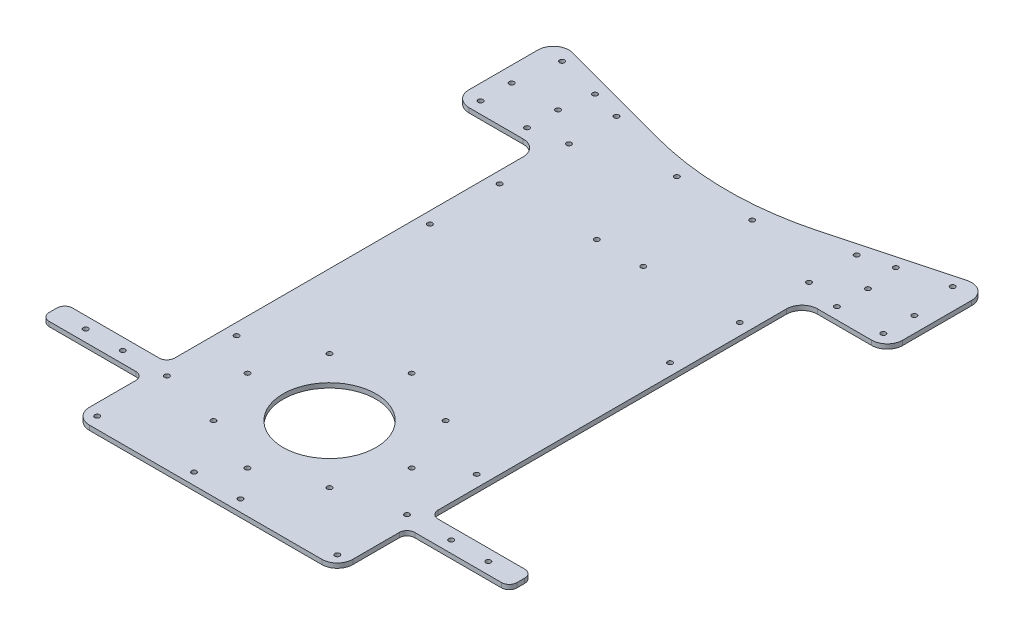
SolidWorks part; units mm, degrees
ref_plane "Front Plane" through (0, 0, 0) normal (0, 0, 1) x (1, 0, 0)
ref_plane "Top Plane" through (0, 0, 0) normal (0, 1, 0) x (1, 0, 0)
ref_plane "Right Plane" through (0, 0, 0) normal (1, 0, 0) x (0, 0, -1)
sketch "Sketch1" plane through (0, 0, 0) normal (0, 1, 0) x (1, 0, 0)
  line L4 (0, 0) -> (170, 0)
  line L5 (0, 0) -> (0, 330) construction
  line L6 (0, 330) -> (170, 330) construction
  line L7 (170, 0) -> (170, 330) construction
  line L8 (85, 330) -> (225, 367.5129)
  line L9 (-55, 367.5129) -> (85, 330)
  line L10 (-55, 367.5129) -> (-55, 300)
  line L11 (-55, 300) -> (0, 300)
  line L12 (225, 300) -> (225, 367.5129)
  line L13 (225, 300) -> (170, 300)
  line L14 (0, 300) -> (0, 0)
  line L15 (170, 300) -> (170, 0)
  dimension "D1" = 30
  dimension "D2" = 330
  dimension "D3" = 15
  dimension "D4" = 15
  dimension "D5" = 55
  dimension "D6" = 170
extrude "Boss-Extrude1" add sketch "Sketch1" along normal blind 3
fillet "Fillet1" radius 200 1 edges at (85, 1.5, -330)
fillet "Fillet2" radius 10 8 edges at (0, 1.5, 0) (170, 1.5, 0) (170, 1.5, -300) (0, 1.5, -300) (-55, 1.5, -300) (225, 1.5, -300) (225, 1.5, -367.5129) (-55, 1.5, -367.5129)
sketch "Sketch2" plane through (0, 3, 0) normal (0, 1, 0) x (1, 0, 0)
  line L0 (85, 337.0552) -> (85, 0) construction
  line L1 (10, 0) -> (160, 0) construction
  arc A0 (33.2362, 343.8701) -> (136.7638, 343.8701) centre (85, 537.0552) ccw construction
  circle A1 centre (85, 80) radius 30
  dimension "D1" = 60
  dimension "D2" = 80
extrude "Cut-Extrude1" cut sketch "Sketch2" against normal through all
sketch "Sketch3" plane through (0, 3, 0) normal (0, 1, 0) x (1, 0, 0)
  line L0 (0, 290) -> (0, 10) construction
  line L1 (0, 45) -> (-66, 45)
  line L2 (0, 45) -> (0, 60)
  line L3 (0, 60) -> (-66, 60)
  line L4 (-66, 45) -> (-66, 60)
  line L5 (-66, 52.5) -> (7.5, 52.5) construction
  line L6 (7.5, 52.5) -> (7.5, 0) construction
  line L7 (10, 0) -> (160, 0) construction
  line L8 (-33, 60) -> (-33, 45) construction
  line L9 (85, 0) -> (85, 337.0552) construction
  line L10 (170, 60) -> (236, 60)
  line L11 (236, 45) -> (236, 60)
  line L12 (170, 45) -> (236, 45)
  line L13 (170, 45) -> (170, 60)
  circle A0 centre (-21, 52.5) radius 1.6
  circle A1 centre (-45, 52.5) radius 1.6
  arc A2 (33.2362, 343.8701) -> (136.7638, 343.8701) centre (85, 537.0552) ccw construction
  circle A3 centre (191, 52.5) radius 1.6
  circle A4 centre (215, 52.5) radius 1.6
  dimension "D2" = 12
  dimension "D6" = 3.2
  dimension "D7" = 12
  dimension "D1" = 66
  dimension "D3" = 7.5
  dimension "D4" = 52.5
  dimension "D5" = 15
extrude "Boss-Extrude2" add sketch "Sketch3" against normal blind 3
fillet "Fillet3" radius 5 8 edges at (236, 1.5, -45) (170, 1.5, -45) (236, 1.5, -60) (170, 1.5, -60) (0, 1.5, -45) (0, 1.5, -60) (-66, 1.5, -60) (-66, 1.5, -45)
sketch "Sketch4" plane through (0, 0, 0) normal (0, -1, 0) x (1, 0, 0)
  circle A0 centre (162.5, -7.5) radius 1.6
  circle A1 centre (162.5, -52.5) radius 1.6
  circle A2 centre (100, -7.5) radius 1.6
  circle A3 centre (70, -7.5) radius 1.6
  circle A4 centre (162.5, -97.5) radius 1.6
  circle A5 centre (162.5, -222.3) radius 1.6
  circle A6 centre (162.5, -267.3) radius 1.6
  circle A7 centre (162.5, -312) radius 1.6
  circle A8 centre (162.5, -342.755) radius 1.6
  circle A9 centre (109.3378, -328.5102) radius 1.6
  circle A10 centre (60.6622, -328.5102) radius 1.6
  circle A11 centre (7.5, -342.755) radius 1.6
  circle A12 centre (7.5, -312) radius 1.6
  circle A13 centre (7.5, -267.3) radius 1.6
  circle A14 centre (7.5, -222.3) radius 1.6
  circle A15 centre (7.5, -97.5) radius 1.6
  circle A16 centre (7.5, -52.5) radius 1.6
  circle A17 centre (7.5, -7.5) radius 1.6
  circle A18 centre (70, -267.5) radius 1.6
  circle A19 centre (100, -267.5) radius 1.6
  dimension "D1" = 3.2
extrude "Cut-Extrude2" cut sketch "Sketch4" against normal through all
sketch "Sketch5" plane through (0, 3, 0) normal (0, 1, 0) x (1, 0, 0)
  circle A0 centre (-40.837, 355.9533) radius 1.6
  circle A1 centre (-11.8592, 348.1888) radius 1.6
  circle A2 centre (182.2342, 348.2893) radius 1.6
  circle A3 centre (211.212, 356.0538) radius 1.6
  dimension "D1" = 3.2
extrude "Cut-Extrude3" cut sketch "Sketch5" against normal through all
sketch "Sketch7" plane through (0, 3, 0) normal (0, 1, 0) x (1, 0, 0)
  line L0 (-55, 335) -> (-5, 335) construction
  line L1 (-55, 354.4806) -> (-55, 310) construction
  line L2 (-5, 335) -> (-5, 300) construction
  line L3 (-45, 300) -> (-10, 300) construction
  line L4 (-45, 327.5) -> (-15, 327.5) construction
  line L5 (-15, 327.5) -> (-15, 307.5) construction
  line L6 (-15, 307.5) -> (-45, 307.5) construction
  line L7 (-45, 307.5) -> (-45, 327.5) construction
  line L8 (85, 337.0552) -> (85, 300) construction
  circle A0 centre (-45, 327.5) radius 1.6
  circle A1 centre (-45, 307.5) radius 1.6
  circle A2 centre (-15, 327.5) radius 1.6
  circle A3 centre (-15, 307.5) radius 1.6
  arc A4 (33.2362, 343.8701) -> (136.7638, 343.8701) centre (85, 537.0552) ccw construction
  circle A5 centre (185, 327.5) radius 1.6
  circle A6 centre (185, 307.5) radius 1.6
  circle A7 centre (215, 307.5) radius 1.6
  circle A8 centre (215, 327.5) radius 1.6
  dimension "D7" = 3.2
  dimension "D1" = 50
  dimension "D2" = 35
  dimension "D3" = 7.5
  dimension "D4" = 10
  dimension "D5" = 7.5
  dimension "D6" = 10
extrude "Cut-Extrude4" cut sketch "Sketch7" against normal through all
sketch "Sketch8" plane through (0, 3, 0) normal (0, 1, 0) x (1, 0, 0)
  line L0 (85, 133) -> (85, 80) construction
  circle A1 centre (85, 133) radius 1.6
  circle A2 centre (85, 80) radius 58 construction
  circle A3 centre (85, 80) radius 53 construction
  circle A4 centre (122.4767, 117.4767) radius 1.6
  circle A5 centre (138, 80) radius 1.6
  circle A6 centre (122.4767, 42.5233) radius 1.6
  circle A7 centre (85, 27) radius 1.6
  circle A8 centre (47.5233, 42.5233) radius 1.6
  circle A9 centre (32, 80) radius 1.6
  circle A10 centre (47.5233, 117.4767) radius 1.6
  point P9 (0, 0)
  point P24 (85, 80)
  dimension "D1" = 116
  dimension "D2" = 5
  dimension "D3" = 3.2
  dimension "D4" = 8
extrude "Cut-Extrude5" cut sketch "Sketch8" against normal blind 10
